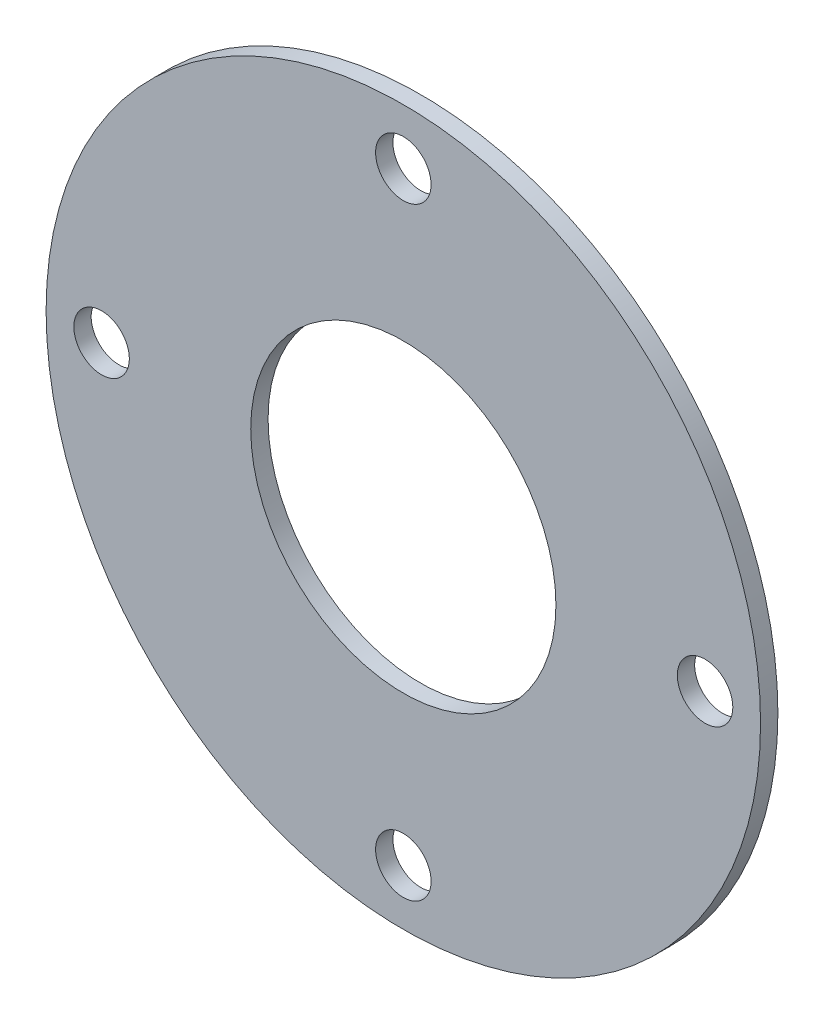
SolidWorks part; units mm, degrees
ref_plane "Спереди" through (0, 0, 0) normal (0, 0, 1) x (1, 0, 0)
ref_plane "Сверху" through (0, 0, 0) normal (0, 1, 0) x (1, 0, 0)
ref_plane "Справа" through (0, 0, 0) normal (1, 0, 0) x (0, 0, -1)
sketch "Эскиз1" plane through (0, 0, 0) normal (0, 0, 1) x (1, 0, 0)
  circle A0 centre (0, 0) radius 51.5
  circle A1 centre (0, 0) radius 22
extrude "Carrier_rear" add sketch "Эскиз1" along normal blind 2.5 from offset 27
sketch "Эскиз2" plane through (0, 0, 0) normal (0, 0, 1) x (1, 0, 0)
  circle A0 centre (43.5, 0) radius 4
  circle A1 centre (0, 43.5) radius 4
  circle A2 centre (-43.5, 0) radius 4
  circle A3 centre (0, -43.5) radius 4
extrude "Through_holes" cut sketch "Эскиз2" against normal mid plane 200
